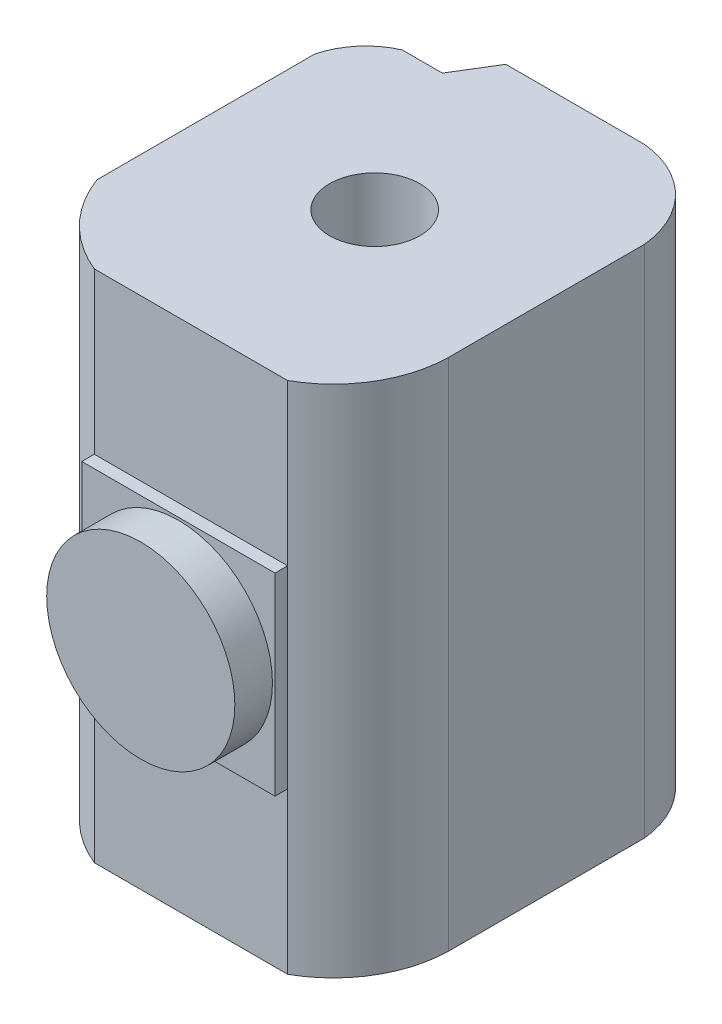
SolidWorks part; units mm, degrees
ref_plane "Front Plane" through (0, 0, 0) normal (0, 0, 1) x (1, 0, 0)
ref_plane "Top Plane" through (0, 0, 0) normal (0, 1, 0) x (1, 0, 0)
ref_plane "Right Plane" through (0, 0, 0) normal (1, 0, 0) x (0, 0, -1)
sketch "Sketch3" plane through (0, 0, 0) normal (0, 1, 0) x (1, 0, 0)
  line L1 (-131.4, -152.64) -> (131.4, -152.64)
  line L2 (-131.4, -152.64) -> (-131.4, 152.64)
  line L3 (-131.4, 152.64) -> (131.4, 152.64)
  line L4 (131.4, -152.64) -> (131.4, 152.64)
  line L5 (-131.4, -152.64) -> (131.4, 152.64) construction
  line L6 (-131.4, 152.64) -> (131.4, -152.64) construction
  point P0 (0, 0)
extrude "Boss-Extrude3" add sketch "Sketch3" along normal blind 410
sketch "Sketch4" plane through (0, 410, 0) normal (0, 1, 0) x (1, 0, 0)
  line L0 (0, 0) -> (0, 36) construction
  line L1 (-131.4, -152.64) -> (-131.4, -90) construction
  line L2 (-131.4, 152.64) -> (-131.4, -152.64) construction
  line L3 (-131.4, -152.64) -> (-70.92, -152.64) construction
  line L4 (-131.4, -152.64) -> (131.4, -152.64) construction
  line L5 (-131.4, -90) -> (-131.4, -152.64)
  line L6 (-131.4, -152.64) -> (-70.92, -152.64)
  line L7 (131.4, -152.64) -> (131.4, -72.72) construction
  line L8 (131.4, -152.64) -> (131.4, 152.64) construction
  line L9 (-131.4, -152.64) -> (83.16, -152.64) construction
  line L10 (83.16, -152.64) -> (131.4, -152.64)
  line L11 (131.4, -152.64) -> (131.4, -72.72)
  line L12 (131.4, -152.64) -> (131.4, 83.52) construction
  line L13 (-131.4, 152.64) -> (-131.4, 121.2871) construction
  line L14 (-99.3727, 121.2871) -> (-67.3455, 121.2871)
  line L15 (131.4, 83.52) -> (131.4, 152.64)
  line L16 (131.4, 152.64) -> (62.28, 152.64)
  line L17 (-131.4, 152.64) -> (-78.12, 152.64) construction
  line L18 (-131.4, 121.2871) -> (-67.3455, 121.2871) construction
  line L19 (-67.3455, 121.2871) -> (-48.1593, 152.64) construction
  line L20 (131.4, 152.64) -> (-131.4, 152.64) construction
  line L21 (131.4, 83.52) -> (-131.4, 83.52) construction
  line L22 (-67.3455, 121.2871) -> (-48.1593, 152.64)
  line L23 (-48.1593, 152.64) -> (-131.4, 152.64)
  line L24 (-131.4, 152.64) -> (-131.4, 83.52)
  arc A0 (-70.92, -152.64) -> (-131.4, -90) centre (-30.0903, -52.7009) cw
  arc A1 (83.16, -152.64) -> (131.4, -72.72) centre (37.7004, -70.6815) ccw
  arc A2 (62.28, 152.64) -> (131.4, 83.52) centre (55.08, 76.32) cw
  arc A3 (-131.4, 83.52) -> (-99.3727, 121.2871) centre (-76.5887, 69.5023) cw
extrude "Cut-Extrude1" cut sketch "Sketch4" against normal through all both and the other way through all
sketch "Sketch5" plane through (0, 410, 0) normal (0, 1, 0) x (1, 0, 0)
  circle A0 centre (0, 0) radius 36
extrude "Cut-Extrude2" cut sketch "Sketch5" against normal through all both and the other way through all
sketch "Sketch6" plane through (0, 0, 152.64) normal (0, 0, 1) x (1, 0, 0)
  line L0 (0, 0) -> (0, 205) construction
  line L1 (0, 205) -> (-70.92, 205) construction
  line L2 (-70.92, 0) -> (-70.92, 410) construction
  line L3 (-70.92, 205) -> (6.12, 205) construction
  line L4 (83.16, 0) -> (83.16, 410) construction
  line L5 (-70.92, 127.96) -> (83.16, 127.96)
  line L6 (-70.92, 127.96) -> (-70.92, 282.04)
  line L7 (-70.92, 282.04) -> (83.16, 282.04)
  line L8 (83.16, 127.96) -> (83.16, 282.04)
  line L9 (-70.92, 127.96) -> (83.16, 282.04) construction
  line L10 (-70.92, 282.04) -> (83.16, 127.96) construction
extrude "Boss-Extrude4" add sketch "Sketch6" along normal blind 10
sketch "Sketch7" plane through (0, 0, 162.64) normal (0, 0, 1) x (1, 0, 0)
  line L0 (83.16, 282.04) -> (-70.92, 127.96) construction
  line L1 (-70.92, 127.96) -> (83.16, 127.96) construction
  line L2 (-70.92, 282.04) -> (-70.92, 127.96) construction
  line L3 (-70.92, 127.96) -> (83.16, 127.96) construction
  line L4 (83.16, 127.96) -> (83.16, 282.04) construction
  line L5 (83.16, 127.96) -> (-70.92, 282.04) construction
  circle A1 centre (6.12, 205) radius 75
extrude "Boss-Extrude5" add sketch "Sketch7" along normal blind 30
